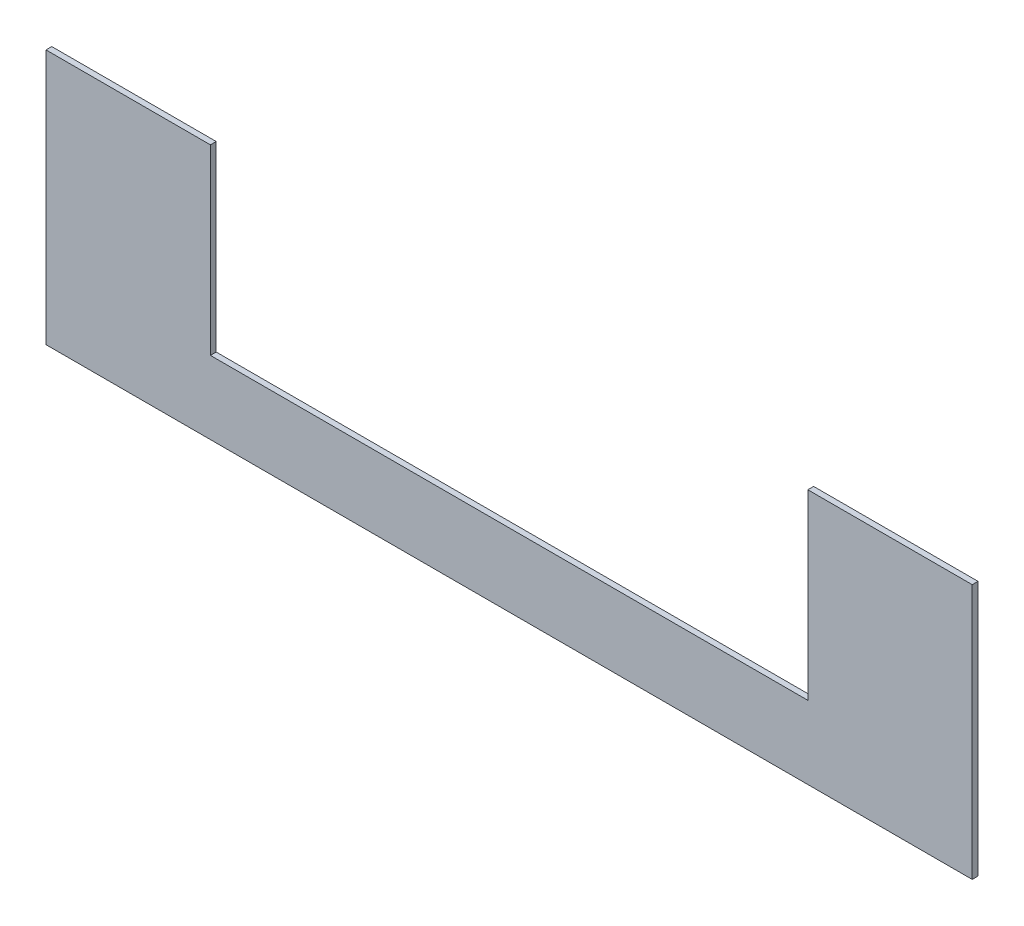
SolidWorks part; units mm, degrees
material "A-Glass Fiber"
ref_plane "Front Plane" through (0, 0, 0) normal (0, 0, 1) x (1, 0, 0)
ref_plane "Top Plane" through (0, 0, 0) normal (0, 1, 0) x (1, 0, 0)
ref_plane "Right Plane" through (0, 0, 0) normal (1, 0, 0) x (0, 0, -1)
sketch "Sketch1" plane through (0, 0, 0) normal (0, 0, 1) x (1, 0, 0)
  line L0 (0.6819, 0.0401) -> (0.6819, -0.4009)
  line L1 (0.6819, -0.4009) -> (0.6819, 0.3691) construction
  line L2 (0.6819, -0.4009) -> (-0.9181, -0.4009)
  line L3 (-0.9181, -0.4009) -> (-0.9181, 0.0401)
  line L4 (-0.9181, 0.3691) -> (-0.9181, -0.4009) construction
  line L5 (-0.9181, 0.0401) -> (-0.6341, 0.0401)
  line L6 (-0.6341, 0.0401) -> (-0.6341, -0.2749)
  line L7 (-0.6341, -0.2749) -> (0.3979, -0.2749)
  line L8 (0.3979, -0.2749) -> (0.3979, 0.0401)
  line L9 (0.3979, 0.0401) -> (0.6819, 0.0401)
  dimension "D1" = 0.284
  dimension "D2" = 0.284
  dimension "D3" = 0.126
  dimension "D4" = 0.315
  dimension "D5" = 0.315
extrude "Boss-Extrude1" add sketch "Sketch1" along normal blind 0.01
